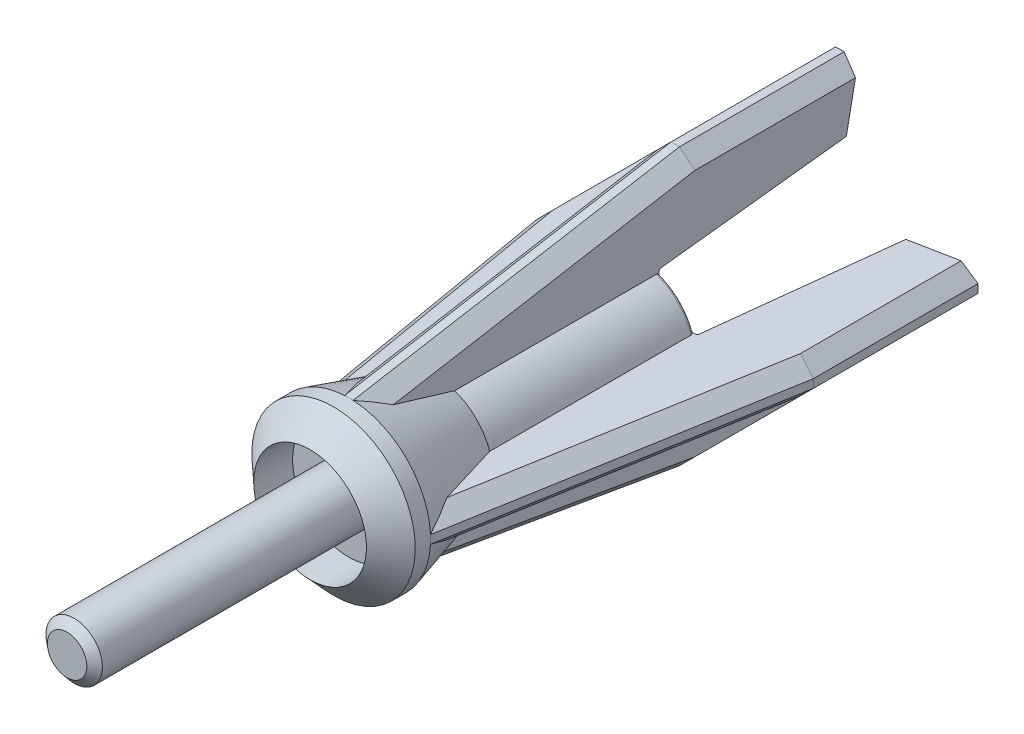
SolidWorks part; units mm, degrees
ref_plane "정면" through (0, 0, 0) normal (0, 0, 1) x (1, 0, 0)
ref_plane "윗면" through (0, 0, 0) normal (0, 1, 0) x (1, 0, 0)
ref_plane "우측면" through (0, 0, 0) normal (1, 0, 0) x (0, 0, -1)
sketch "스케치1" plane through (0, 0, 0) normal (0, 1, 0) x (1, 0, 0)
  line L0 (0, 0) -> (1.5, 0.3499)
  line L1 (1, -10) -> (1, -19.7483)
  line L2 (1, -10) -> (2, -10)
  line L3 (0, 0) -> (0, -11.4371) construction
  line L4 (2, -10) -> (2, 0.3499)
  line L5 (1, -19.7483) -> (0.7, -20)
  line L6 (0.7, -20) -> (0, -20)
  line L7 (0, -20) -> (0, 0)
  line L8 (1.5, 0.3499) -> (2, 0.3499)
  dimension "D1" = 2
  dimension "D2" = 20
  dimension "D3" = 10
  dimension "D4" = 0.5
  dimension "D5" = 4
  dimension "D6" = 140
  dimension "D7" = 0.7
revolve "회전1" add sketch "스케치1" angle 360 about L3
sketch "스케치2" plane through (0, 0, 0) normal (1, 0, 0) x (0, 0, -1)
  line L0 (-10, 2.9) -> (1.5755, 4.9)
  line L1 (1.5755, 4.9) -> (7.4206, 4.9)
  line L2 (7.4206, 4.9) -> (7, 2.7597)
  line L3 (7, 2.7597) -> (0.3499, 2)
  line L4 (0.3499, 2) -> (0.3499, 1.4)
  line L5 (0.3499, -2) -> (0.3499, 2) construction
  line L6 (0.3499, 1.4) -> (-10, 1.4)
  line L7 (-10, 2) -> (-10, -2) construction
  line L8 (-10, 1.4) -> (-10, 2.9)
  dimension "D1" = 4.9
  dimension "D2" = 17
  dimension "D3" = 1.5
  dimension "D4" = 1.4
extrude "보스-돌출1" add sketch "스케치2" along normal mid plane 1.3
chamfer "모따기1" distance 0.5 angle 45 4 edges at (-0.65, 3.9, 4.2123) (0.65, 3.9, 4.2123) (-0.65, 4.9, -4.498) (0.65, 4.9, -4.498)
pattern_circular "원형 패턴2" count 4 over 360 about axis through (0, 0, 0) along (0, 0, 1) of "모따기1", "보스-돌출1"
fillet "필렛1" radius 0.1 7 edges at (0, 2, -0.3499) (2, 0, -0.3499) (0, -2, -0.3499) (1.4142, -1.4142, -0.3499) (1.4142, 1.4142, -0.3499) (-1.4142, -1.4142, -0.3499) (-1.4142, 1.4142, -0.3499)
sketch "스케치3" plane through (0, 0, 0) normal (1, 0, 0) x (0, 0, -1)
  line L0 (0, 0) -> (-10, 0)
  line L1 (-10, 1) -> (-10, -1) construction
  line L2 (-10, 0) -> (-10, 2)
  line L3 (-10, 2) -> (-11.3788, 2)
  line L4 (-11.3788, 2) -> (-10.5468, 2.9)
  line L5 (-10.5468, 2.9) -> (-10, 2.9)
  line L6 (-10, 2.9) -> (0, 0)
  line L7 (0, 0) -> (0.0385, 0.039)
  dimension "D1" = 2
revolve "회전2" add sketch "스케치3" angle 360 about L0
